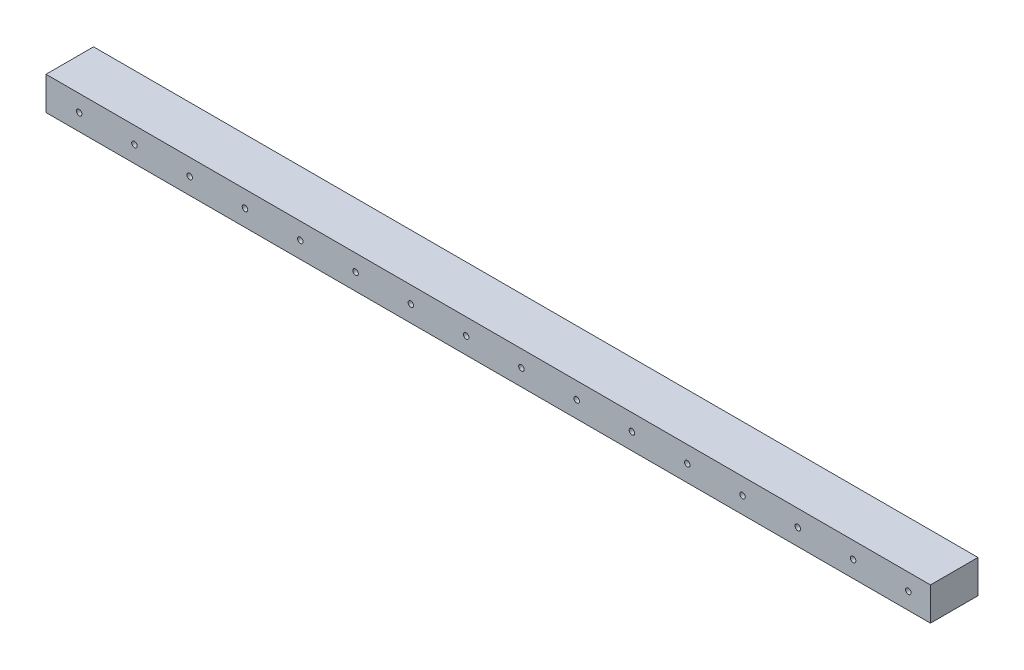
SolidWorks part; units mm, degrees
ref_plane "前视基准面" through (0, 0, 0) normal (0, 0, 1) x (1, 0, 0)
ref_plane "上视基准面" through (0, 0, 0) normal (0, 1, 0) x (1, 0, 0)
ref_plane "右视基准面" through (0, 0, 0) normal (1, 0, 0) x (0, 0, -1)
ref_plane "基准面4" through (0, 7.5, 0) normal (0, 1, 0) x (1, 0, 0)
sketch "草图1" plane through (0, 7.5, 0) normal (0, 1, 0) x (1, 0, 0)
  line L0 (-200, -21.5) -> (200, -21.5)
  line L1 (200, -21.5) -> (200, 0)
  line L2 (200, 0) -> (-200, 0)
  line L3 (-200, 0) -> (-200, -21.5)
extrude "凸台-拉伸1" add sketch "草图1" against normal blind 15
hole_wizard "Ø2.5 (2.5) 直径孔1" positions "草图3" profile "草图2" hole size "Ø2.5" standard "ANSI Metric"
sketch "草图3" plane through (0, 0, 21.5) normal (0, 0, 1) x (1, 0, 0)
  point P0 (-185, 0)
  point P1 (-160, 0)
  point P2 (-135, 0)
  point P3 (-110, 0)
  point P4 (-85, 0)
  point P5 (-60, 0)
  point P6 (-35, 0)
  point P7 (-10, 0)
  point P8 (15, 0)
  point P9 (40, 0)
  point P10 (65, 0)
  point P11 (90, 0)
  point P12 (115, 0)
  point P13 (140, 0)
  point P14 (190, 0)
  point P15 (165, 0)
sketch "草图2" plane through (-185, 0, 21.5) normal (1, 0, 0) x (0, -1, 0)
  line L0 (0, 0) -> (0, 9.2511)
  line L1 (0, 9.2511) -> (1.25, 8.5)
  line L2 (1.25, 8.5) -> (1.25, 0)
  line L5 (1.25, 0) -> (0, 0)
  line L10 (0, 9.2511) -> (-1.25, 8.5) construction
  line L11 (0, -6.35) -> (0, 107.95) construction
  dimension "孔直径" = 2.5
  dimension "孔深度" = 8.5
  dimension "导头角度" = 118
